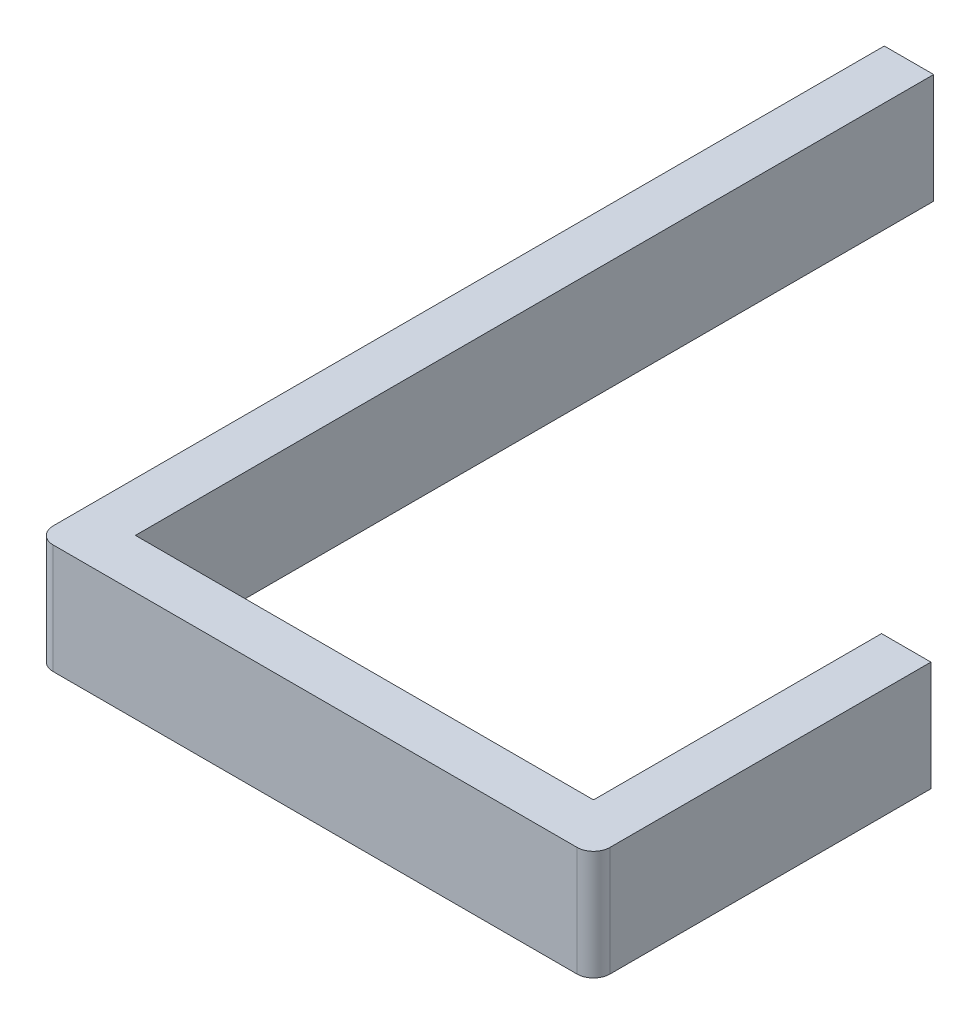
SolidWorks part; units mm, degrees
ref_plane "前视基准面" through (0, 0, 0) normal (0, 0, 1) x (1, 0, 0)
ref_plane "上视基准面" through (0, 0, 0) normal (0, 1, 0) x (1, 0, 0)
ref_plane "右视基准面" through (0, 0, 0) normal (1, 0, 0) x (0, 0, -1)
other "Configuration Table"
sketch "草图1" plane through (0, 0, 0) normal (0, 1, 0) x (1, 0, 0)
  line L1 (0, 0) -> (9, 0)
  line L2 (0, 0) -> (0, -105.5)
  line L3 (0, -105.5) -> (9, -105.5)
  line L4 (9, 0) -> (9, -105.5)
  line L5 (0, -105.5) -> (92.5, -105.5)
  line L6 (0, -105.5) -> (0, -114.5)
  line L7 (0, -114.5) -> (92.5, -114.5)
  line L8 (92.5, -105.5) -> (92.5, -114.5)
  line L9 (92.5, -114.5) -> (101.5, -114.5)
  line L10 (92.5, -114.5) -> (92.5, -53)
  line L11 (92.5, -53) -> (101.5, -53)
  line L12 (101.5, -114.5) -> (101.5, -53)
  dimension "D1" = 105.5
  dimension "D2" = 83.5
  dimension "D3" = 52.5
  dimension "D4" = 9
  dimension "D5" = 9
  dimension "D6" = 9
extrude "凸台-拉伸1" add sketch "草图1" along normal blind 20 contours L4 L1 L2 L3 | L8 L5 L3 L6 L7 | L9 L12 L11 L10 L8
fillet "圆角1" radius 3 2 edges at (101.5, 10, 114.5) (0, 10, 114.5)
sketch "草图2" plane through (0, 0, 0) normal (-1, 0, 0) x (0, 0, 1)
  line L1 (0, 20) -> (-40, 20)
  line L2 (0, 20) -> (0, 0)
  line L3 (0, 0) -> (-40, 0)
  line L4 (-40, 20) -> (-40, 0)
  dimension "D1" = 40
extrude "凸台-拉伸2" add sketch "草图2" against normal up to surface (9 mm away) up to face at (9, 10, 52.75)
